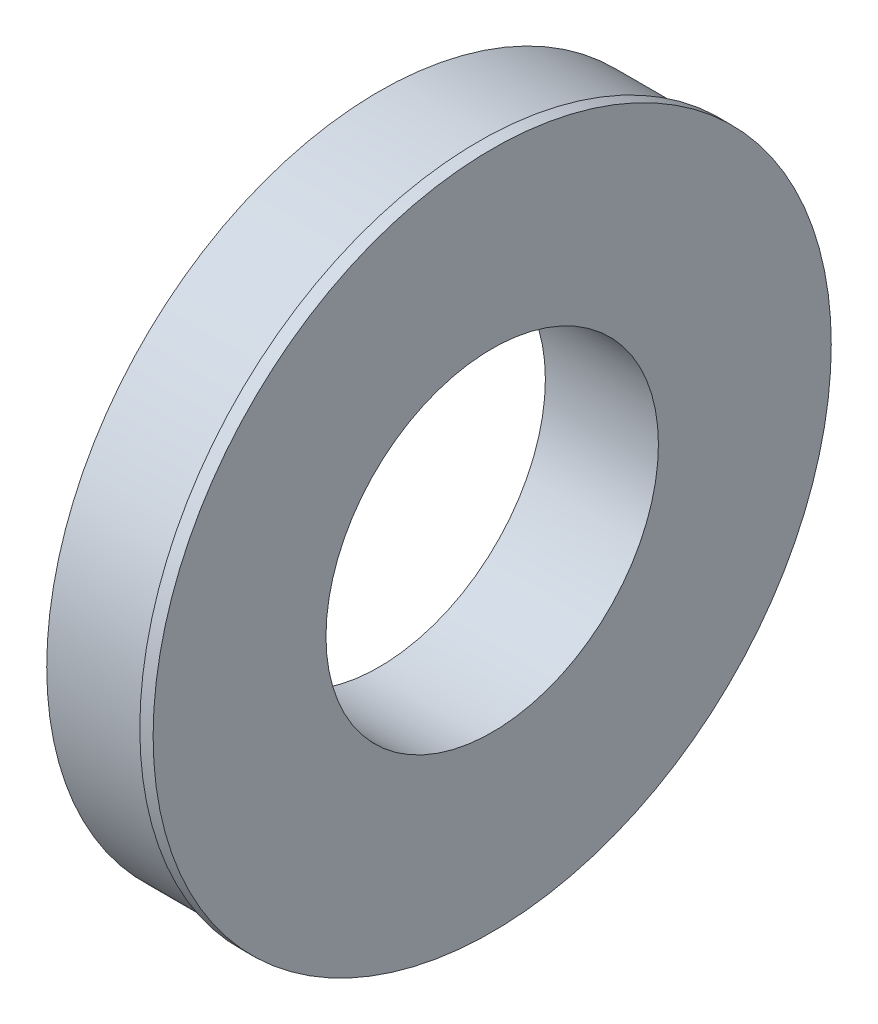
SolidWorks part; units mm, degrees
material "Commercial Bronze, UNS C22000 (90-10 Bronze)"
ref_plane "Front Plane" through (0, 0, 0) normal (0, 0, 1) x (1, 0, 0)
ref_plane "Top Plane" through (0, 0, 0) normal (0, 1, 0) x (1, 0, 0)
ref_plane "Right Plane" through (0, 0, 0) normal (1, 0, 0) x (0, 0, -1)
sketch "Sketch1" plane through (0, 0, 0) normal (1, 0, 0) x (0, 0, -1)
  circle A0 centre (0, 0) radius 63.5
  circle A1 centre (0, 0) radius 31.75
  dimension "D1" = 63.5
  dimension "D2" = 127
extrude "Boss-Extrude1" add sketch "Sketch1" along normal blind 19.05
sketch "Sketch2" plane through (19.05, 0, 0) normal (1, 0, 0) x (0, 0, -1)
  circle A0 centre (0, 0) radius 64.77
  circle A1 centre (0, 0) radius 31.75
  dimension "D1" = 129.54
  dimension "D2" = 63.5
extrude "Boss-Extrude2" add sketch "Sketch2" along normal blind 2.54
